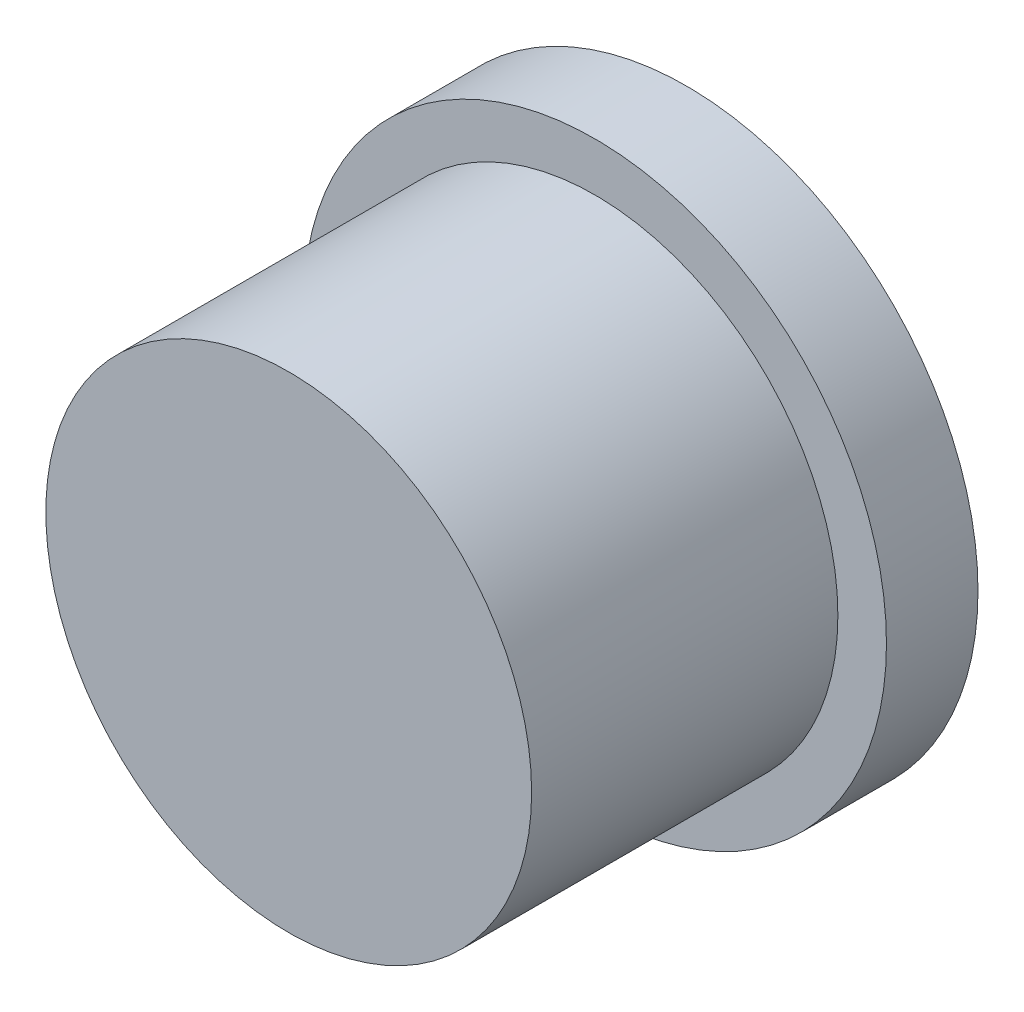
SolidWorks part; units mm, degrees
ref_plane "Front Plane" through (0, 0, 0) normal (0, 0, 1) x (1, 0, 0)
ref_plane "Top Plane" through (0, 0, 0) normal (0, 1, 0) x (1, 0, 0)
ref_plane "Right Plane" through (0, 0, 0) normal (1, 0, 0) x (0, 0, -1)
sketch "Sketch1" plane through (0, 0, 0) normal (0, 0, 1) x (1, 0, 0)
  circle A0 centre (0, 0) radius 3.81
  dimension "D1" = 7.62
extrude "Boss-Extrude1" add sketch "Sketch1" along normal blind 1.1963
sketch "Sketch2" plane through (0, 0, 1.1963) normal (0, 0, 1) x (1, 0, 0)
  circle A0 centre (0, 0) radius 3.175
  dimension "D1" = 6.35
extrude "Boss-Extrude2" add sketch "Sketch2" along normal blind 4.003
